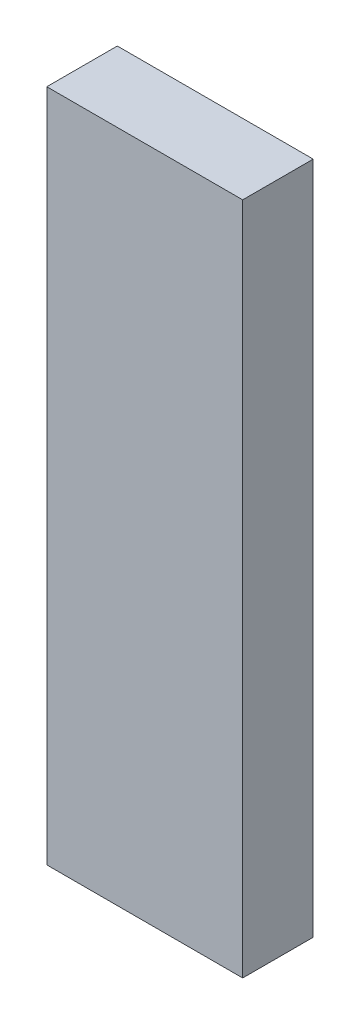
SolidWorks part; units mm, degrees
ref_plane "Front Plane" through (0, 0, 0) normal (0, 0, 1) x (1, 0, 0)
ref_plane "Top Plane" through (0, 0, 0) normal (0, 1, 0) x (1, 0, 0)
ref_plane "Right Plane" through (0, 0, 0) normal (1, 0, 0) x (0, 0, -1)
sketch "Sketch1" plane through (0, 0, 0) normal (0, 0, 1) x (1, 0, 0)
  line L1 (-25, 86) -> (25, 86)
  line L2 (-25, 86) -> (-25, -86)
  line L3 (-25, -86) -> (25, -86)
  line L4 (25, 86) -> (25, -86)
  line L5 (-25, 86) -> (25, -86) construction
  line L6 (-25, -86) -> (25, 86) construction
  point P0 (0, 0)
  dimension "D1" = 50
  dimension "D2" = 172
extrude "Boss-Extrude1" add sketch "Sketch1" along normal blind 18
